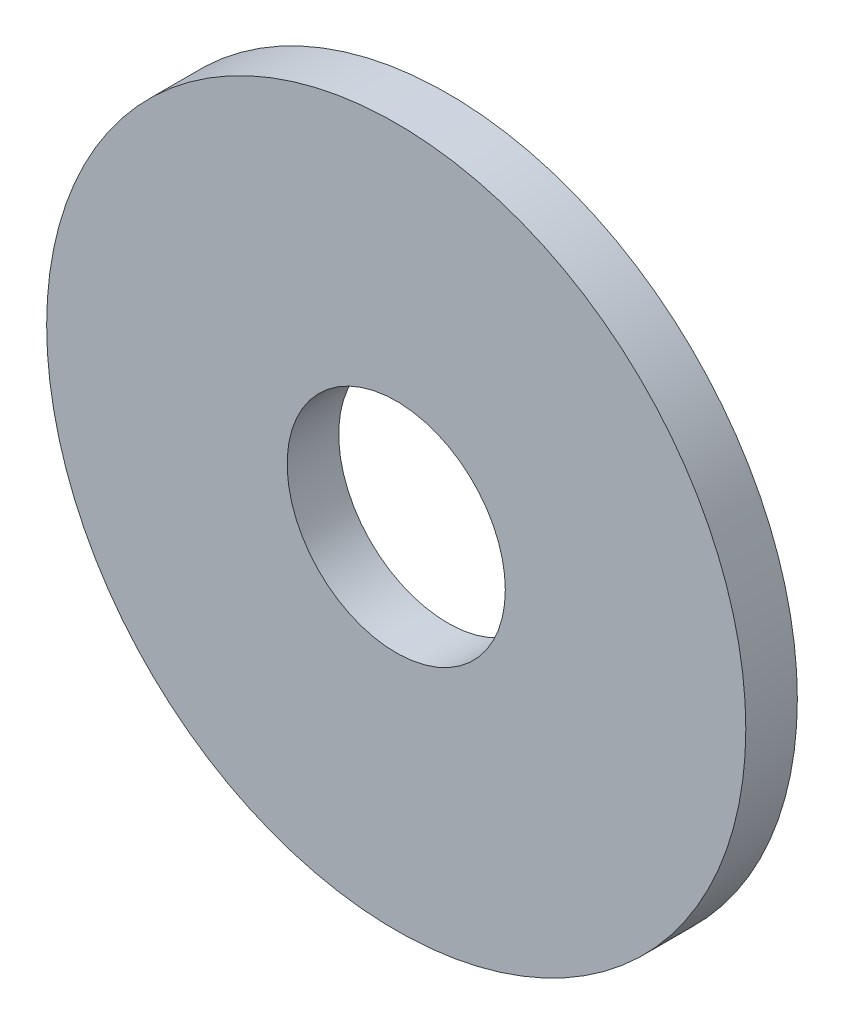
SolidWorks part; units mm, degrees
ref_plane "Front Plane" through (0, 0, 0) normal (0, 0, 1) x (1, 0, 0)
ref_plane "Top Plane" through (0, 0, 0) normal (0, 1, 0) x (1, 0, 0)
ref_plane "Right Plane" through (0, 0, 0) normal (1, 0, 0) x (0, 0, -1)
sketch "Sketch1" plane through (0, 0, 0) normal (0, 0, 1) x (1, 0, 0)
  circle A0 centre (-5.0652, 3.5095) radius 10.175
  circle A1 centre (-5.0652, 3.5095) radius 3.175
  point P4 (0, 0)
  dimension "D1" = 20.35
  dimension "D2" = 6.35
extrude "Boss-Extrude1" add sketch "Sketch1" along normal blind 1.5
